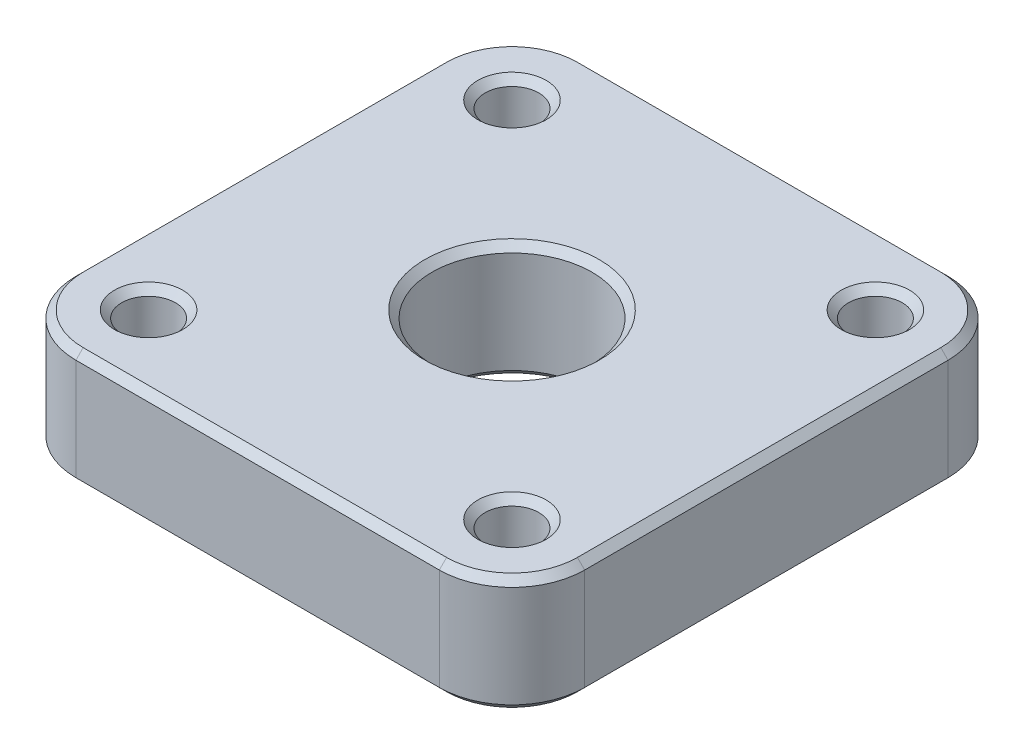
SolidWorks part; units mm, degrees
ref_plane "Спереди" through (0, 0, 0) normal (0, 0, 1) x (1, 0, 0)
ref_plane "Сверху" through (0, 0, 0) normal (0, 1, 0) x (1, 0, 0)
ref_plane "Справа" through (0, 0, 0) normal (1, 0, 0) x (0, 0, -1)
sketch "Эскиз1" plane through (0, 0, 0) normal (0, 1, 0) x (1, 0, 0)
  line L1 (-35, -35) -> (35, -35)
  line L2 (-35, -35) -> (-35, 35)
  line L3 (-35, 35) -> (35, 35)
  line L4 (35, -35) -> (35, 35)
  line L5 (0, 35) -> (0, -35) construction
  line L6 (-35, 0) -> (35, 0) construction
  point P0 (0, 0)
  dimension "D1" = 70
extrude "Бобышка-Вытянуть1" add sketch "Эскиз1" along normal blind 16
sketch "Эскиз2" plane through (0, 16, 0) normal (0, 1, 0) x (1, 0, 0)
  line L1 (-25, -25) -> (25, -25) construction
  line L2 (-25, -25) -> (-25, 25) construction
  line L3 (-25, 25) -> (25, 25) construction
  line L4 (25, -25) -> (25, 25) construction
  line L5 (0, 25) -> (0, -25) construction
  line L6 (-25, 0) -> (25, 0) construction
  circle A0 centre (0, 0) radius 11
  circle A1 centre (-25, 25) radius 3.7
  circle A2 centre (25, 25) radius 3.7
  circle A3 centre (25, -25) radius 3.7
  circle A4 centre (-25, -25) radius 3.7
  point P0 (0, 0)
  dimension "D2" = 7.4
  dimension "D1" = 50
extrude "Вырез-Вытянуть1" cut sketch "Эскиз2" against normal through all
fillet "Скругление1" radius 10 4 edges at (-35, 8, 35) (-35, 8, -35) (35, 8, 35) (35, 8, -35)
chamfer "Фаска1" distance 1 angle 45 26 edges at (0, 0, -35) (-35, 0, 0) (0, 0, 35) (35, 0, 0) (0, 0, 11) (-25, 0, -21.3) (25, 0, -21.3) (25, 0, 28.7) (-25, 0, 28.7) (0, 16, 35) (-35, 16, 0) (0, 16, -35) (35, 16, 0) (0, 16, 11) (-25, 16, -21.3) (25, 16, -21.3) (25, 16, 28.7) (-25, 16, 28.7) (32.0711, 0, 32.0711) (32.0711, 0, -32.0711) (-32.0711, 0, -32.0711) (-32.0711, 0, 32.0711) (-32.0711, 16, -32.0711) (32.0711, 16, -32.0711) (32.0711, 16, 32.0711) (-32.0711, 16, 32.0711)
